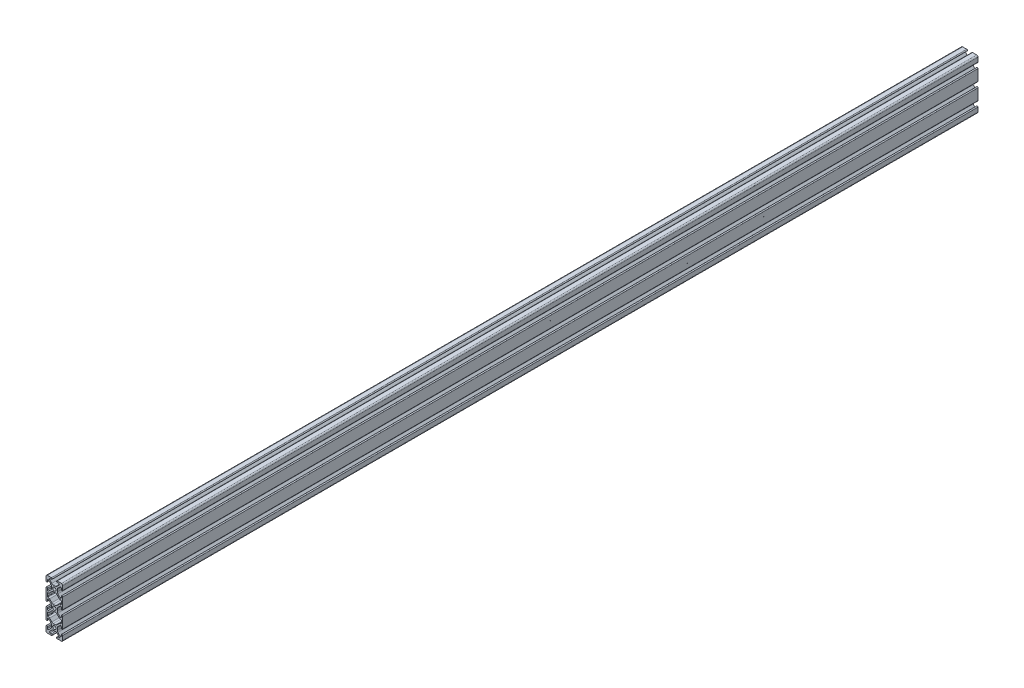
SolidWorks part; units mm, degrees
material "6105-T5"
ref_plane "Front Plane" through (0, 0, 0) normal (0, 0, 1) x (1, 0, 0)
ref_plane "Top Plane" through (0, 0, 0) normal (0, 1, 0) x (1, 0, 0)
ref_plane "Right Plane" through (0, 0, 0) normal (1, 0, 0) x (0, 0, -1)
sketch "Sketch1" plane through (0, 0, 0) normal (0, 0, 1) x (1, 0, 0)
  line L0 (9.3698, 15.43) -> (9.6, 15.43)
  line L1 (10.36, 14.67) -> (10.36, 10.3305)
  line L2 (9.6, 9.5705) -> (9.3698, 9.5705)
  line L3 (7.1282, 8.6419) -> (3.79, 5.3032)
  line L4 (1.5485, 4.3748) -> (-1.5485, 4.3748)
  line L5 (-3.79, 5.3032) -> (-7.1283, 8.6415)
  line L6 (-9.3698, 9.57) -> (-9.6, 9.57)
  line L7 (-10.36, 10.33) -> (-10.36, 14.6695)
  line L8 (-9.6, 15.4295) -> (-9.3698, 15.4295)
  line L9 (-7.1282, 16.3581) -> (-3.79, 19.6968)
  line L10 (-1.5485, 20.6252) -> (1.5485, 20.6252)
  line L11 (3.79, 19.6968) -> (7.1283, 16.3585)
  line L12 (9.3698, 40.43) -> (9.6, 40.43)
  line L13 (10.36, 39.67) -> (10.36, 35.3305)
  line L14 (9.6, 34.5705) -> (9.3698, 34.5705)
  line L15 (7.1282, 33.6419) -> (3.79, 30.3032)
  line L16 (1.5485, 29.3748) -> (-1.5485, 29.3748)
  line L17 (-3.79, 30.3032) -> (-7.1283, 33.6415)
  line L18 (-9.3698, 34.57) -> (-9.6, 34.57)
  line L19 (-10.36, 35.33) -> (-10.36, 39.6695)
  line L20 (-9.6, 40.4295) -> (-9.3698, 40.4295)
  line L21 (-7.1282, 41.3581) -> (-3.79, 44.6968)
  line L22 (-1.5485, 45.6252) -> (1.5485, 45.6252)
  line L23 (3.79, 44.6968) -> (7.1283, 41.3585)
  line L24 (10.36, 56.43) -> (10.36, 54.32)
  line L25 (12.5, 54.32) -> (12.5, 60.5)
  line L26 (10.5, 62.5) -> (4.32, 62.5)
  line L27 (4.32, 60.36) -> (6.4295, 60.36)
  line L28 (7.1394, 58.6531) -> (3.79, 55.3032)
  line L29 (1.5485, 54.3748) -> (-1.5485, 54.3748)
  line L30 (-3.79, 55.3032) -> (-7.1384, 58.6516)
  line L31 (-6.43, 60.36) -> (-4.32, 60.36)
  line L32 (-4.32, 62.5) -> (-10.5, 62.5)
  line L33 (-12.5, 60.5) -> (-12.5, 54.32)
  line L34 (-10.36, 54.32) -> (-10.36, 56.4295)
  line L35 (-8.6531, 57.1394) -> (-5.3032, 53.79)
  line L36 (-4.3748, 51.5485) -> (-4.3748, 48.4515)
  line L37 (-5.3032, 46.21) -> (-8.6516, 42.8616)
  line L38 (-10.36, 43.57) -> (-10.36, 45.68)
  line L39 (-12.5, 45.68) -> (-12.5, 29.32)
  line L40 (-10.36, 29.32) -> (-10.36, 31.4295)
  line L41 (-8.6531, 32.1394) -> (-5.3032, 28.79)
  line L42 (-4.3748, 26.5485) -> (-4.3748, 23.4515)
  line L43 (-5.3032, 21.21) -> (-8.6516, 17.8616)
  line L44 (-10.36, 18.57) -> (-10.36, 20.68)
  line L45 (-12.5, 20.68) -> (-12.5, 4.32)
  line L46 (-10.36, 4.32) -> (-10.36, 6.4295)
  line L47 (-8.6531, 7.1394) -> (-5.3032, 3.79)
  line L48 (-4.3748, 1.5485) -> (-4.3748, -1.5485)
  line L49 (-5.3032, -3.79) -> (-8.6516, -7.1384)
  line L50 (-10.36, -6.43) -> (-10.36, -4.32)
  line L51 (-12.5, -4.32) -> (-12.5, -10.5)
  line L52 (-10.5, -12.5) -> (-4.32, -12.5)
  line L53 (-4.32, -10.36) -> (-6.4295, -10.36)
  line L54 (-7.1394, -8.6531) -> (-3.79, -5.3032)
  line L55 (-1.5485, -4.3748) -> (1.5485, -4.3748)
  line L56 (3.79, -5.3032) -> (7.1384, -8.6516)
  line L57 (6.43, -10.36) -> (4.32, -10.36)
  line L58 (4.32, -12.5) -> (10.5, -12.5)
  line L59 (12.5, -10.5) -> (12.5, -4.32)
  line L60 (10.36, -4.32) -> (10.36, -6.4295)
  line L61 (8.6531, -7.1394) -> (5.3032, -3.79)
  line L62 (4.3748, -1.5485) -> (4.3748, 1.5485)
  line L63 (5.3032, 3.79) -> (8.6516, 7.1384)
  line L64 (10.36, 6.4301) -> (10.36, 4.32)
  line L65 (12.5, 4.32) -> (12.5, 20.68)
  line L66 (10.36, 20.68) -> (10.36, 18.5705)
  line L67 (8.6531, 17.8606) -> (5.3032, 21.21)
  line L68 (4.3748, 23.4515) -> (4.3748, 26.5485)
  line L69 (5.3032, 28.79) -> (8.6516, 32.1384)
  line L70 (10.36, 31.43) -> (10.36, 29.32)
  line L71 (12.5, 29.32) -> (12.5, 45.68)
  line L72 (10.36, 45.68) -> (10.36, 43.5705)
  line L73 (8.6531, 42.8606) -> (5.3032, 46.21)
  line L74 (4.3748, 48.4515) -> (4.3748, 51.5485)
  line L75 (5.3032, 53.79) -> (8.6516, 57.1384)
  circle A0 centre (0, 0) radius 2.5
  arc A1 (7.1283, 16.3585) -> (9.3698, 15.43) centre (9.3698, 18.6) ccw
  arc A2 (10.36, 14.67) -> (9.6, 15.43) centre (9.6, 14.67) ccw
  arc A3 (9.6, 9.5705) -> (10.36, 10.3305) centre (9.6, 10.3305) ccw
  arc A4 (9.3698, 9.5705) -> (7.1282, 8.6419) centre (9.3698, 6.4005) ccw
  arc A5 (1.5485, 4.3748) -> (3.79, 5.3032) centre (1.5485, 7.5448) ccw
  arc A6 (-3.79, 5.3032) -> (-1.5485, 4.3748) centre (-1.5485, 7.5448) ccw
  arc A7 (-7.1283, 8.6415) -> (-9.3698, 9.57) centre (-9.3698, 6.4) ccw
  arc A8 (-10.36, 10.33) -> (-9.6, 9.57) centre (-9.6, 10.33) ccw
  arc A9 (-9.6, 15.4295) -> (-10.36, 14.6695) centre (-9.6, 14.6695) ccw
  arc A10 (-9.3698, 15.4295) -> (-7.1282, 16.3581) centre (-9.3698, 18.5995) ccw
  arc A11 (-1.5485, 20.6252) -> (-3.79, 19.6968) centre (-1.5485, 17.4552) ccw
  arc A12 (3.79, 19.6968) -> (1.5485, 20.6252) centre (1.5485, 17.4552) ccw
  circle A13 centre (0, 25) radius 2.5
  circle A14 centre (0, 50) radius 2.5
  arc A15 (7.1283, 41.3585) -> (9.3698, 40.43) centre (9.3698, 43.6) ccw
  arc A16 (10.36, 39.67) -> (9.6, 40.43) centre (9.6, 39.67) ccw
  arc A17 (9.6, 34.5705) -> (10.36, 35.3305) centre (9.6, 35.3305) ccw
  arc A18 (9.3698, 34.5705) -> (7.1282, 33.6419) centre (9.3698, 31.4005) ccw
  arc A19 (1.5485, 29.3748) -> (3.79, 30.3032) centre (1.5485, 32.5448) ccw
  arc A20 (-3.79, 30.3032) -> (-1.5485, 29.3748) centre (-1.5485, 32.5448) ccw
  arc A21 (-7.1283, 33.6415) -> (-9.3698, 34.57) centre (-9.3698, 31.4) ccw
  arc A22 (-10.36, 35.33) -> (-9.6, 34.57) centre (-9.6, 35.33) ccw
  arc A23 (-9.6, 40.4295) -> (-10.36, 39.6695) centre (-9.6, 39.6695) ccw
  arc A24 (-9.3698, 40.4295) -> (-7.1282, 41.3581) centre (-9.3698, 43.5995) ccw
  arc A25 (-1.5485, 45.6252) -> (-3.79, 44.6968) centre (-1.5485, 42.4552) ccw
  arc A26 (3.79, 44.6968) -> (1.5485, 45.6252) centre (1.5485, 42.4552) ccw
  arc A27 (10.36, 54.32) -> (12.5, 54.32) centre (11.43, 54.32) ccw
  arc A28 (12.5, 60.5) -> (10.5, 62.5) centre (10.5, 60.5) ccw
  arc A29 (4.32, 62.5) -> (4.32, 60.36) centre (4.32, 61.43) ccw
  arc A30 (7.1394, 58.6531) -> (6.4295, 60.36) centre (6.4285, 59.3585) ccw
  arc A31 (1.5485, 54.3748) -> (3.79, 55.3032) centre (1.5485, 57.5448) ccw
  arc A32 (-3.79, 55.3032) -> (-1.5485, 54.3748) centre (-1.5485, 57.5448) ccw
  arc A33 (-6.43, 60.36) -> (-7.1384, 58.6516) centre (-6.429, 59.3585) ccw
  arc A34 (-4.32, 60.36) -> (-4.32, 62.5) centre (-4.32, 61.43) ccw
  arc A35 (-10.5, 62.5) -> (-12.5, 60.5) centre (-10.5, 60.5) ccw
  arc A36 (-12.5, 54.32) -> (-10.36, 54.32) centre (-11.43, 54.32) ccw
  arc A37 (-8.6531, 57.1394) -> (-10.36, 56.4295) centre (-9.3585, 56.4285) ccw
  arc A38 (-4.3748, 51.5485) -> (-5.3032, 53.79) centre (-7.5448, 51.5485) ccw
  arc A39 (-5.3032, 46.21) -> (-4.3748, 48.4515) centre (-7.5448, 48.4515) ccw
  arc A40 (-10.36, 43.57) -> (-8.6516, 42.8616) centre (-9.3585, 43.571) ccw
  arc A41 (-10.36, 45.68) -> (-12.5, 45.68) centre (-11.43, 45.68) ccw
  arc A42 (-12.5, 29.32) -> (-10.36, 29.32) centre (-11.43, 29.32) ccw
  arc A43 (-8.6531, 32.1394) -> (-10.36, 31.4295) centre (-9.3585, 31.4285) ccw
  arc A44 (-4.3748, 26.5485) -> (-5.3032, 28.79) centre (-7.5448, 26.5485) ccw
  arc A45 (-5.3032, 21.21) -> (-4.3748, 23.4515) centre (-7.5448, 23.4515) ccw
  arc A46 (-10.36, 18.57) -> (-8.6516, 17.8616) centre (-9.3585, 18.571) ccw
  arc A47 (-10.36, 20.68) -> (-12.5, 20.68) centre (-11.43, 20.68) ccw
  arc A48 (-12.5, 4.32) -> (-10.36, 4.32) centre (-11.43, 4.32) ccw
  arc A49 (-8.6531, 7.1394) -> (-10.36, 6.4295) centre (-9.3585, 6.4285) ccw
  arc A50 (-4.3748, 1.5485) -> (-5.3032, 3.79) centre (-7.5448, 1.5485) ccw
  arc A51 (-5.3032, -3.79) -> (-4.3748, -1.5485) centre (-7.5448, -1.5485) ccw
  arc A52 (-10.36, -6.43) -> (-8.6516, -7.1384) centre (-9.3585, -6.429) ccw
  arc A53 (-10.36, -4.32) -> (-12.5, -4.32) centre (-11.43, -4.32) ccw
  arc A54 (-12.5, -10.5) -> (-10.5, -12.5) centre (-10.5, -10.5) ccw
  arc A55 (-4.32, -12.5) -> (-4.32, -10.36) centre (-4.32, -11.43) ccw
  arc A56 (-7.1394, -8.6531) -> (-6.4295, -10.36) centre (-6.4285, -9.3585) ccw
  arc A57 (-1.5485, -4.3748) -> (-3.79, -5.3032) centre (-1.5485, -7.5448) ccw
  arc A58 (3.79, -5.3032) -> (1.5485, -4.3748) centre (1.5485, -7.5448) ccw
  arc A59 (6.43, -10.36) -> (7.1384, -8.6516) centre (6.429, -9.3585) ccw
  arc A60 (4.32, -10.36) -> (4.32, -12.5) centre (4.32, -11.43) ccw
  arc A61 (10.5, -12.5) -> (12.5, -10.5) centre (10.5, -10.5) ccw
  arc A62 (12.5, -4.32) -> (10.36, -4.32) centre (11.43, -4.32) ccw
  arc A63 (8.6531, -7.1394) -> (10.36, -6.4295) centre (9.3585, -6.4285) ccw
  arc A64 (4.3748, -1.5485) -> (5.3032, -3.79) centre (7.5448, -1.5485) ccw
  arc A65 (5.3032, 3.79) -> (4.3748, 1.5485) centre (7.5448, 1.5485) ccw
  arc A66 (10.36, 6.4301) -> (8.6516, 7.1384) centre (9.3585, 6.429) ccw
  arc A67 (10.36, 4.32) -> (12.5, 4.32) centre (11.43, 4.32) ccw
  arc A68 (12.5, 20.68) -> (10.36, 20.68) centre (11.43, 20.68) ccw
  arc A69 (8.6531, 17.8606) -> (10.36, 18.5705) centre (9.3585, 18.5715) ccw
  arc A70 (4.3748, 23.4515) -> (5.3032, 21.21) centre (7.5448, 23.4515) ccw
  arc A71 (5.3032, 28.79) -> (4.3748, 26.5485) centre (7.5448, 26.5485) ccw
  arc A72 (10.36, 31.43) -> (8.6516, 32.1384) centre (9.3585, 31.429) ccw
  arc A73 (10.36, 29.32) -> (12.5, 29.32) centre (11.43, 29.32) ccw
  arc A74 (12.5, 45.68) -> (10.36, 45.68) centre (11.43, 45.68) ccw
  arc A75 (8.6531, 42.8606) -> (10.36, 43.5705) centre (9.3585, 43.5715) ccw
  arc A76 (4.3748, 48.4515) -> (5.3032, 46.21) centre (7.5448, 48.4515) ccw
  arc A77 (5.3032, 53.79) -> (4.3748, 51.5485) centre (7.5448, 51.5485) ccw
  arc A78 (10.36, 56.43) -> (8.6516, 57.1384) centre (9.3585, 56.429) ccw
  point P0 (-12.5, 62.5)
  point P1 (0, 62.5)
  point P2 (12.5, 62.5)
  point P237 (12.5, 50)
  point P238 (-12.5, 50)
  point P239 (0, 50)
  point P240 (12.5, 37.5)
  point P241 (0, 37.5)
  point P242 (-12.5, 37.5)
  point P243 (-12.5, 25)
  point P244 (0, 25)
  point P245 (12.5, 25)
  point P246 (12.5, 12.5)
  point P247 (0, 12.5)
  point P248 (-12.5, 12.5)
  point P249 (-12.5, 0)
  point P250 (12.5, 0)
  point P251 (-12.5, -12.5)
  point P252 (0, -12.5)
  point P253 (12.5, -12.5)
extrude "Extrude1" add sketch "Sketch1" against normal blind 1371.6
